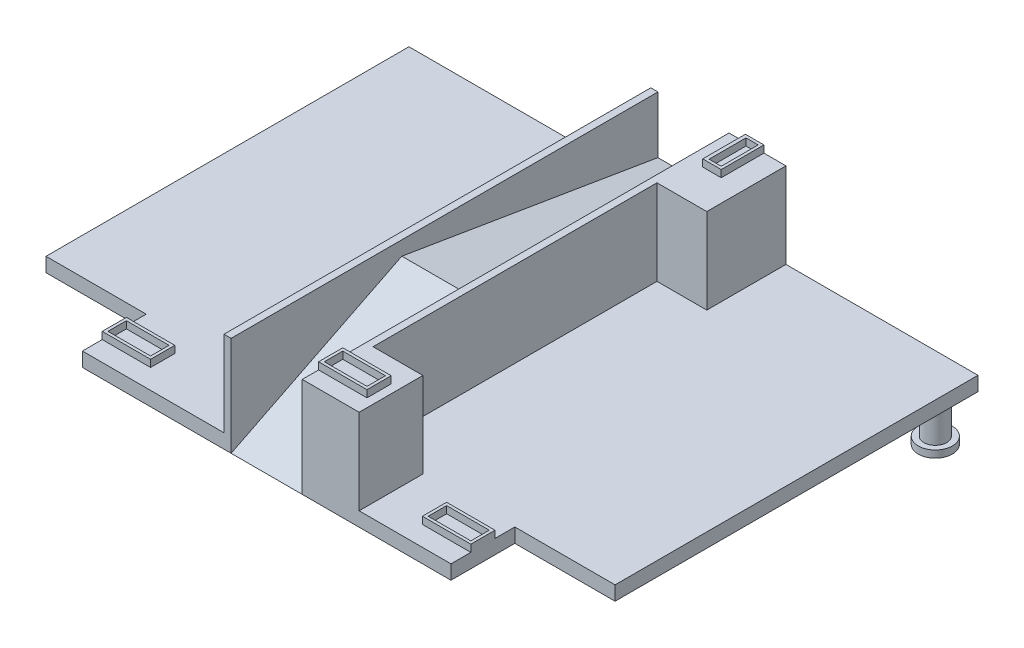
SolidWorks part; units mm, degrees
ref_plane "Front Plane" through (0, 0, 0) normal (0, 0, 1) x (1, 0, 0)
ref_plane "Top Plane" through (0, 0, 0) normal (0, 1, 0) x (1, 0, 0)
ref_plane "Right Plane" through (0, 0, 0) normal (1, 0, 0) x (0, 0, -1)
sketch "Sketch1" plane through (0, 0, 0) normal (0, 1, 0) x (1, 0, 0)
  line L1 (-100.4558, 255.2091) -> (299.5442, 255.2091)
  line L2 (-100.4558, 255.2091) -> (-100.4558, 0.0925)
  line L3 (-30, -44.7909) -> (229.0884, -44.7909)
  line L5 (-100.4558, 0.0925) -> (-30, 0.0925)
  line L8 (-30, 0.0925) -> (-30, -44.7909)
  line L23 (99.5442, 255.2091) -> (99.5442, -44.7909) construction
  line L32 (299.5442, 0.0925) -> (229.0884, 0.0925)
  line L33 (299.5442, 255.2091) -> (299.5442, 0.0925)
  line L34 (229.0884, 0.0925) -> (229.0884, -44.7909)
  point P32 (199.0884, -22.3492)
  dimension "D3" = 200
  dimension "D4" = 300
  dimension "D2" = 44.8834
  dimension "D11" = 70.4558
  dimension "D12" = 129.5442
extrude "Boss-Extrude3" add sketch "Sketch1" along normal blind 10
sketch "Sketch2" plane through (0, 10, 0) normal (0, 1, 0) x (1, 0, 0)
  line L0 (-30, 0.0925) -> (-30, -44.7909) construction
  line L1 (-30, -13.8492) -> (4, -13.8492)
  line L3 (-30, -13.8492) -> (-30, -30.8492)
  line L4 (-30, -30.8492) -> (4, -30.8492)
  line L5 (4, -13.8492) -> (4, -30.8492)
  line L6 (-13, -13.8492) -> (-13, -30.8492) construction
  line L7 (-28, -15.8492) -> (2, -15.8492)
  line L8 (-28, -15.8492) -> (-28, -28.8492)
  line L9 (-28, -28.8492) -> (2, -28.8492)
  line L10 (2, -15.8492) -> (2, -28.8492)
  line L11 (4, -22.3492) -> (-30, -22.3492) construction
  line L12 (-30, -44.7909) -> (229.0884, -44.7909) construction
  line L13 (99.5442, 255.2091) -> (99.5442, -44.7909) construction
  line L14 (299.5442, 255.2091) -> (-100.4558, 255.2091) construction
  line L15 (195.0884, -22.3492) -> (229.0884, -22.3492) construction
  line L16 (212.0884, -13.8492) -> (212.0884, -30.8492) construction
  line L17 (197.0884, -15.8492) -> (197.0884, -28.8492)
  line L18 (227.0884, -28.8492) -> (197.0884, -28.8492)
  line L19 (227.0884, -15.8492) -> (227.0884, -28.8492)
  line L20 (227.0884, -15.8492) -> (197.0884, -15.8492)
  line L21 (195.0884, -13.8492) -> (195.0884, -30.8492)
  line L22 (229.0884, -30.8492) -> (195.0884, -30.8492)
  line L23 (229.0884, -13.8492) -> (229.0884, -30.8492)
  line L24 (229.0884, -13.8492) -> (195.0884, -13.8492)
  dimension "D1" = 2
  dimension "D2" = 2
  dimension "D3" = 2
  dimension "D4" = 2
  dimension "D5" = 30
  dimension "D6" = 13
  dimension "D7" = 22.4417
extrude "Boss-Extrude4" add sketch "Sketch2" along normal blind 5
sketch "Sketch3" plane through (0, 10, 0) normal (0, 1, 0) x (1, 0, 0)
  line L0 (99.5442, 255.2091) -> (99.5442, -44.7909) construction
  line L1 (299.5442, 255.2091) -> (-100.4558, 255.2091) construction
  line L2 (-30, -44.7909) -> (229.0884, -44.7909) construction
  line L3 (74.5442, -44.7909) -> (74.5442, 75.2091)
  line L4 (74.5442, 75.2091) -> (124.5442, 75.2091)
  line L5 (124.5442, 75.2091) -> (124.5442, -44.7909)
  line L22 (195.0884, -30.8492) -> (195.0884, -13.8492)
  line L23 (195.0884, -13.8492) -> (229.0884, -13.8492)
  line L24 (229.0884, -13.8492) -> (229.0884, 0.0925)
  line L25 (229.0884, 0.0925) -> (299.5442, 0.0925)
  line L26 (299.5442, 0.0925) -> (299.5442, 255.2091)
  line L27 (299.5442, 255.2091) -> (-100.4558, 255.2091)
  line L28 (-100.4558, 255.2091) -> (-100.4558, 0.0925)
  line L29 (-100.4558, 0.0925) -> (-30, 0.0925)
  line L30 (-30, 0.0925) -> (-30, -13.8492)
  line L31 (-30, -13.8492) -> (4, -13.8492)
  line L32 (4, -13.8492) -> (4, -30.8492)
  line L33 (4, -30.8492) -> (-30, -30.8492)
  line L34 (-30, -30.8492) -> (-30, -44.7909)
  line L35 (-30, -44.7909) -> (229.0884, -44.7909)
  line L36 (229.0884, -44.7909) -> (229.0884, -30.8492)
  line L37 (229.0884, -30.8492) -> (195.0884, -30.8492)
  line L51 (74.5442, -44.7909) -> (124.5442, -44.7909)
  dimension "D1" = 50
  dimension "D2" = 25
  dimension "D3" = 120
extrude "Boss-Extrude5" add sketch "Sketch3" along normal blind 50
sketch "Sketch4" plane through (124.5442, 0, 0) normal (1, 0, 0) x (0, 0, -1)
  line L2 (-44.7909, 60) -> (75.2091, 60)
  line L3 (75.2091, 60) -> (-44.7909, 0)
  line L4 (-44.7909, 60) -> (-44.7909, 0)
extrude "Cut-Extrude2" cut sketch "Sketch4" against normal up to vertex (50 mm away)
sketch "Sketch5" plane through (0, 10, 0) normal (0, 1, 0) x (1, 0, 0)
  line L0 (74.5442, 75.2091) -> (74.5442, 255.2091)
  line L1 (299.5442, 255.2091) -> (-100.4558, 255.2091) construction
  line L2 (74.5442, 255.2091) -> (124.5442, 255.2091)
  line L3 (124.5442, 255.2091) -> (124.5442, 75.2091)
  line L4 (74.5442, 75.2091) -> (124.5442, 75.2091)
  line L5 (74.5442, 75.2091) -> (74.5442, -24.7909) construction
extrude "Boss-Extrude6" add sketch "Sketch5" along normal blind 50
sketch "Sketch6" plane through (124.5442, 0, 0) normal (1, 0, 0) x (0, 0, -1)
  line L2 (75.2091, 60) -> (255.2091, 60)
  line L3 (255.2091, 60) -> (255.2091, 30)
  line L4 (255.2091, 60) -> (255.2091, 10) construction
  line L5 (255.2091, 30) -> (75.2091, 60)
  dimension "D1" = 30
extrude "Cut-Extrude3" cut sketch "Sketch6" against normal through all contours L2 L3 L5
sketch "Sketch7" plane through (0, 0, 0) normal (0, 1, 0) x (1, 0, 0)
  line L0 (69.5442, 255.2091) -> (69.5442, -44.7909)
  line L1 (74.5442, 255.2091) -> (-100.4558, 255.2091) construction
  line L2 (-30, -44.7909) -> (74.5442, -44.7909) construction
  line L3 (69.5442, -44.7909) -> (74.5442, -44.7909)
  line L4 (74.5442, -44.7909) -> (74.5442, 255.2091)
  line L5 (74.5442, 255.2091) -> (74.5442, -24.7909) construction
  line L6 (74.5442, 255.2091) -> (124.5442, 255.2091) construction
  line L7 (74.5442, 255.2091) -> (69.5442, 255.2091)
  line L8 (124.5442, 255.2091) -> (129.5442, 255.2091)
  line L9 (299.5442, 255.2091) -> (124.5442, 255.2091) construction
  line L10 (129.5442, 255.2091) -> (129.5442, -44.7909)
  line L11 (124.5442, -44.7909) -> (229.0884, -44.7909) construction
  line L12 (129.5442, -44.7909) -> (124.5442, -44.7909)
  line L13 (124.5442, -44.7909) -> (124.5442, 255.2091)
  line L14 (129.5442, -44.7909) -> (164.5442, -44.7909)
  line L15 (124.5442, -44.7909) -> (229.0884, -44.7909) construction
  line L16 (164.5442, -44.7909) -> (164.5442, 0)
  line L17 (164.5442, 0) -> (129.5442, 0)
  dimension "D1" = 5
  dimension "D2" = 5
  dimension "D3" = 35
extrude "Boss-Extrude7" add sketch "Sketch7" along normal blind 70 contours L16 L17 L10 L14 | L7 L0 L3 L4
sketch "Sketch9" plane through (0, 70, 0) normal (0, 1, 0) x (1, 0, 0)
  line L0 (124.5442, -44.7909) -> (124.5442, 75.2091) construction
  line L1 (124.5442, -16.2909) -> (158.5442, -16.2909)
  line L2 (124.5442, -16.2909) -> (124.5442, -33.2909)
  line L3 (124.5442, -33.2909) -> (158.5442, -33.2909)
  line L4 (158.5442, -16.2909) -> (158.5442, -33.2909)
  line L5 (158.5442, -24.7909) -> (124.5442, -24.7909) construction
  line L6 (126.5442, -18.2909) -> (156.5442, -18.2909)
  line L7 (126.5442, -18.2909) -> (126.5442, -31.2909)
  line L8 (126.5442, -31.2909) -> (156.5442, -31.2909)
  line L9 (156.5442, -18.2909) -> (156.5442, -31.2909)
  line L10 (141.5442, -16.2909) -> (141.5442, -35.4954) construction
  line L11 (164.5442, -44.7909) -> (124.5442, -44.7909) construction
  dimension "D1" = 2
  dimension "D2" = 2
  dimension "D3" = 2
  dimension "D4" = 2
  dimension "D5" = 30
  dimension "D6" = 13
  dimension "D7" = 20
extrude "Boss-Extrude8" add sketch "Sketch9" along normal blind 5 contours L2 L1 L4 L3 | L7 L6 L9 L8
sketch "Sketch10" plane through (129.5442, 0, 0) normal (1, 0, 0) x (0, 0, -1)
  line L0 (199.5615, 70) -> (199.5615, 10)
  line L1 (255.2091, 70) -> (0, 70) construction
  line L2 (0, 10) -> (255.2091, 10) construction
  line L3 (199.5615, 10) -> (255.2091, 10)
  line L4 (255.2091, 10) -> (255.2091, 70)
  line L5 (255.2091, 70) -> (199.5615, 70)
extrude "Boss-Extrude9" add sketch "Sketch10" along normal blind 35
sketch "Sketch13" plane through (0, 70, 0) normal (0, 1, 0) x (1, 0, 0)
  line L0 (136.0527, 255.2091) -> (149.0527, 255.2091)
  line L1 (124.5442, 255.2091) -> (164.5442, 255.2091) construction
  line L2 (149.0527, 255.2091) -> (149.0527, 225.2091)
  line L3 (149.0527, 225.2091) -> (136.0527, 225.2091)
  line L4 (136.0527, 225.2091) -> (136.0527, 255.2091)
  line L5 (138.4599, 253.2091) -> (147.0527, 253.2091)
  line L6 (147.0527, 253.2091) -> (147.0527, 227.2091)
  line L7 (147.0527, 227.2091) -> (138.4599, 227.2091)
  line L8 (138.4599, 227.2091) -> (138.4599, 253.2091)
  dimension "D1" = 13
  dimension "D2" = 13
  dimension "D3" = 30
  dimension "D4" = 2
  dimension "D5" = 2
  dimension "D6" = 2
extrude "Boss-Extrude11" add sketch "Sketch13" along normal blind 5
sketch "Sketch14" plane through (0, 0, 0) normal (0, -1, 0) x (1, 0, 0)
  line L0 (299.5442, -0.0925) -> (299.5442, -255.2091) construction
  line L1 (299.5442, -255.2091) -> (-100.4558, -255.2091) construction
  circle A0 centre (284.5442, -240.2091) radius 8
  dimension "D1" = 15
  dimension "D2" = 15
extrude "Boss-Extrude12" add sketch "Sketch14" along normal blind 27
sketch "Sketch16" plane through (0, 0, 0) normal (0, -1, 0) x (1, 0, 0)
  line L0 (-100.4558, -255.2091) -> (-100.4558, -0.0925) construction
  line L1 (299.5442, -255.2091) -> (-100.4558, -255.2091) construction
  circle A0 centre (-85.4558, -240.2091) radius 8
  dimension "D1" = 15
  dimension "D2" = 15
extrude "Boss-Extrude13" add sketch "Sketch16" along normal blind 27
sketch "Sketch17" plane through (0, -27, 0) normal (0, -1, 0) x (1, 0, 0)
  circle A0 centre (284.5442, -240.2091) radius 12
extrude "Boss-Extrude14" add sketch "Sketch17" along normal blind 5
sketch "Sketch18" plane through (0, -27, 0) normal (0, -1, 0) x (1, 0, 0)
  circle A0 centre (-85.4558, -240.2091) radius 12
extrude "Boss-Extrude15" add sketch "Sketch18" along normal blind 5
equation "\"draggingScrewDiameter\"= 2"
equation "\"chassisWidth\"= 400"
equation "\"D3@Sketch1\"=0.5 * \"chassisWidth\""
equation "\"chassisLength\"=300"
equation "\"D4@Sketch1\"=\"chassisLength\""
equation "\"wheelDepth\"=44.8834"
equation "\"D2@Sketch1\"=\"wheelDepth\""
equation "\"wheelWidth\"=70.4558"
equation "\"D11@Sketch1\"=\"wheelWidth\""
equation "\"D12@Sketch1\"=(0.5 * \"chassisWidth\") - \"wheelWidth\""
equation "\"baseThickness\"=10"
equation "\"D1@Boss-Extrude3\"=\"baseThickness\""
equation "\"D7@Sketch2\"=\"wheelDepth\" * 0.5"
equation "\"rampLength\"=120"
equation "\"D3@Sketch3\"=\"rampLength\""
equation "\"rampHeight\"=50"
equation "\"D1@Boss-Extrude5\"=\"rampHeight\""
equation "\"D1@Boss-Extrude6\"=\"rampHeight\""
equation "\"dumpHeight\"=30"
equation "\"D1@Sketch6\"=\"dumpHeight\""
